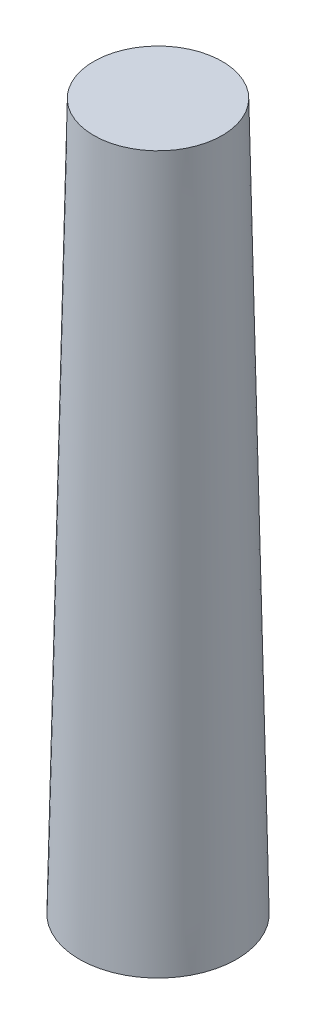
SolidWorks part; units mm, degrees
material "ABS"
ref_plane "Front Plane" through (0, 0, 0) normal (0, 0, 1) x (1, 0, 0)
ref_plane "Top Plane" through (0, 0, 0) normal (0, 1, 0) x (1, 0, 0)
ref_plane "Right Plane" through (0, 0, 0) normal (1, 0, 0) x (0, 0, -1)
sketch "Sketch1" plane through (0, 0, 0) normal (0, 1, 0) x (1, 0, 0)
  circle A0 centre (0, 0) radius 1.8669
  dimension "D1" = 3.7338
ref_plane "Plane1" through (0, 16.764, 0) normal (0, 1, 0) x (1, 0, 0)
sketch "Sketch2" plane through (0, 16.764, 0) normal (0, 1, 0) x (1, 0, 0)
  circle A0 centre (0, 0) radius 1.524
  dimension "D1" = 3.048
loft "Loft1" add profiles "Sketch2", "Sketch1"
